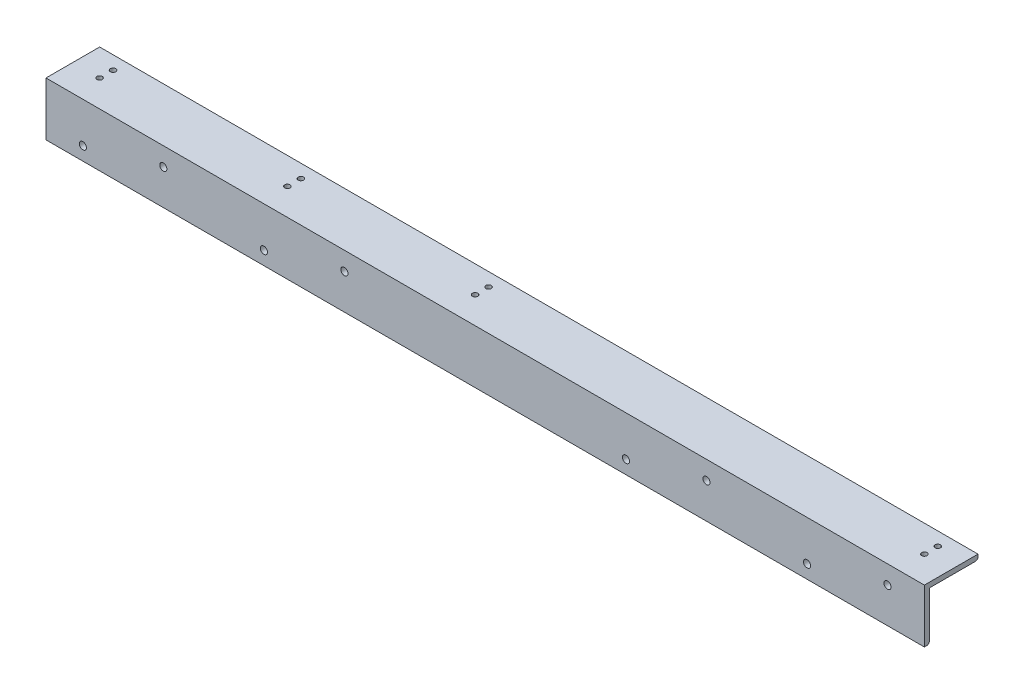
SolidWorks part; units mm, degrees
material "6061 Alloy"
ref_plane "Front Plane" through (0, 0, 0) normal (0, 0, 1) x (1, 0, 0)
ref_plane "Top Plane" through (0, 0, 0) normal (0, 1, 0) x (1, 0, 0)
ref_plane "Right Plane" through (0, 0, 0) normal (1, 0, 0) x (0, 0, -1)
sketch "Sketch1" plane through (0, 0, 0) normal (1, 0, 0) x (0, 0, -1)
  line L0 (0, 0) -> (50.8, 0)
  line L1 (50.8, 0) -> (50.8, -2.2225)
  line L2 (48.26, -4.7625) -> (4.7625, -4.7625)
  line L3 (4.7625, -4.7625) -> (4.7625, -48.26)
  line L4 (2.2225, -50.8) -> (0, -50.8)
  line L5 (0, -50.8) -> (0, 0)
  arc A0 (50.8, -2.2225) -> (48.26, -4.7625) centre (48.26, -2.2225) cw
  arc A1 (4.7625, -48.26) -> (2.2225, -50.8) centre (2.2225, -48.26) cw
  point P11 (4.7625, -50.8)
  dimension "D3" = 2.54
  dimension "D1" = 50.8
  dimension "D2" = 4.7625
extrude "Boss-Extrude1" add sketch "Sketch1" along normal mid plane 831.85
hole_wizard "1/4 Clearance Hole1" positions "Sketch3" profile "Sketch4" hole size "1/4" standard "ANSI Inch" end condition up to next
sketch "Sketch3" plane through (0, 0, -4.7625) normal (0, 0, -1) x (-1, 0, 0)
  line L0 (-415.925, -17.4625) -> (415.925, -17.4625) construction
  line L1 (-415.925, -48.26) -> (-415.925, -4.7625) construction
  line L2 (415.925, -48.26) -> (415.925, -4.7625) construction
  line L4 (-415.925, -38.1) -> (415.925, -38.1) construction
  line L6 (-415.925, -4.7625) -> (415.925, -4.7625) construction
  line L7 (-415.925, -50.8) -> (415.925, -50.8) construction
  point P17 (-381, -17.4625)
  point P19 (-304.8, -38.1)
  dimension "D1" = 12.7
  dimension "D2" = 12.7
  dimension "D3" = 34.925
  dimension "D4" = 76.2
sketch "Sketch4" plane through (381, -17.4625, -4.7625) normal (1, 0, 0) x (0, 1, 0)
  line L0 (0, 0) -> (0, 4.7635)
  line L1 (0, 4.7635) -> (3.3782, 4.7635)
  line L2 (3.3782, 4.7635) -> (3.3782, 0)
  line L5 (3.3782, 0) -> (0, 0)
  line L11 (0, -6.35) -> (0, 107.95) construction
  dimension "Thru Hole Dia." = 6.7564
  dimension "Thru Hole Depth" = 4.7635
pattern_linear "LPattern1" count 5 spacing 171.45 along (-1, 0, 0) skipping (2, 0) of "1/4 Clearance Hole1"
hole_wizard "#10 Clearance Hole2" positions "Sketch6" profile "Sketch5" hole size "#10" standard "ANSI Inch"
sketch "Sketch6" plane through (0, 0, 0) normal (0, 1, 0) x (1, 0, 0)
  line L0 (-415.925, 25.4) -> (-34.925, 25.4) construction
  line L1 (-415.925, 50.8) -> (-415.925, 0) construction
  line L3 (-34.925, 38.1) -> (-415.925, 38.1) construction
  line L5 (415.925, 50.8) -> (-415.925, 50.8) construction
  line L6 (390.525, 38.1) -> (390.525, 25.4) construction
  line L7 (415.925, 50.8) -> (415.925, 0) construction
  point P13 (-34.925, 25.4)
  point P15 (-34.925, 38.1)
  point P17 (-212.725, 38.1)
  point P19 (-212.725, 25.4)
  point P21 (-390.525, 25.4)
  point P23 (-390.525, 38.1)
  point P29 (390.525, 38.1)
  point P30 (390.525, 25.4)
  dimension "D1" = 12.7
  dimension "D2" = 12.7
  dimension "D3" = 25.4
  dimension "D4" = 381
  dimension "D5" = 203.2
  dimension "D6" = 25.4
  dimension "D7" = 12.7
sketch "Sketch5" plane through (-34.925, 0, -25.4) normal (1, 0, 0) x (0, 0, 1)
  line L0 (0, 0) -> (0, 6.2953)
  line L1 (0, 6.2953) -> (2.5527, 4.7615)
  line L2 (2.5527, 4.7615) -> (2.5527, 0)
  line L5 (2.5527, 0) -> (0, 0)
  line L10 (0, 6.2953) -> (-2.5527, 4.7615) construction
  line L11 (0, -6.35) -> (0, 107.95) construction
  dimension "Hole Dia." = 5.1054
  dimension "Hole Depth" = 4.7615
  dimension "Drill Angle" = 118
